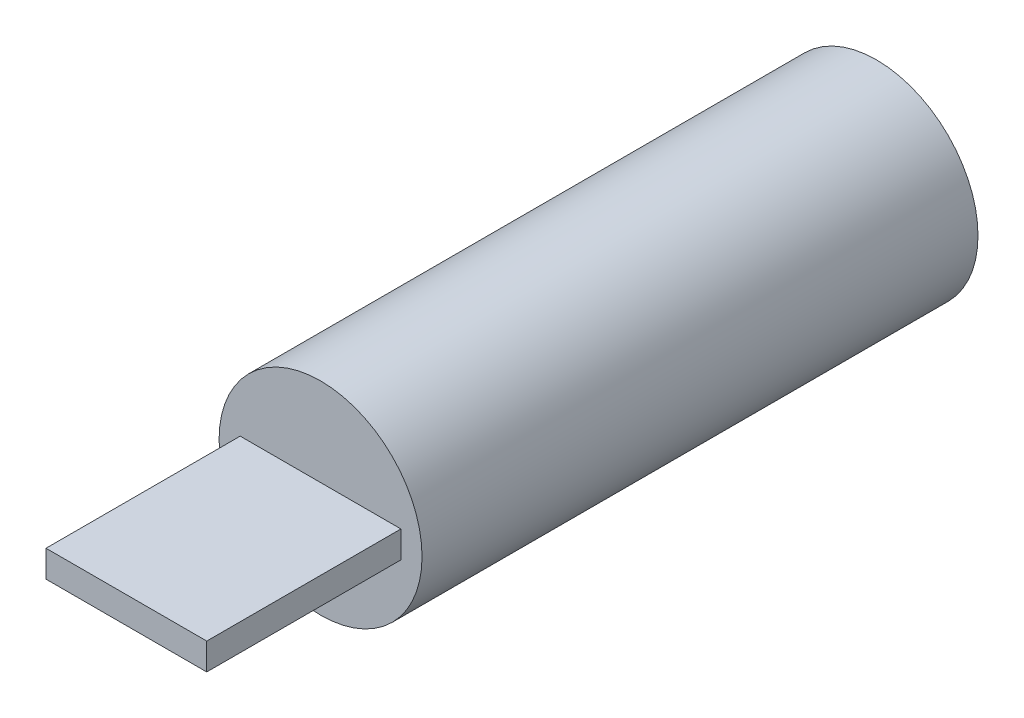
SolidWorks part; units mm, degrees
material "Custom Plastic"
ref_plane "X-Y Datum" through (0, 0, 0) normal (0, 0, 1) x (1, 0, 0)
ref_plane "X-Z Datum" through (0, 0, 0) normal (0, 1, 0) x (1, 0, 0)
ref_plane "Y-Z Datum" through (0, 0, 0) normal (1, 0, 0) x (0, 0, -1)
sketch "Sketch1" plane through (0, 0, 0) normal (0, 0, 1) x (1, 0, 0)
  circle A0 centre (0, 0) radius 12.0269
extrude "Boss-Extrude1" add sketch "Sketch1" along normal blind 65.8876
sketch "Sketch2" plane through (0, 0, 65.8876) normal (0, 0, 1) x (1, 0, 0)
  line L1 (-9.525, -1.5875) -> (9.525, -1.5875)
  line L2 (-9.525, -1.5875) -> (-9.525, 1.5875)
  line L3 (-9.525, 1.5875) -> (9.525, 1.5875)
  line L4 (9.525, -1.5875) -> (9.525, 1.5875)
  line L5 (-9.525, -1.5875) -> (9.525, 1.5875) construction
  line L6 (-9.525, 1.5875) -> (9.525, -1.5875) construction
  point P0 (0, 0)
extrude "Boss-Extrude2" add sketch "Sketch2" along normal blind 23.0124
